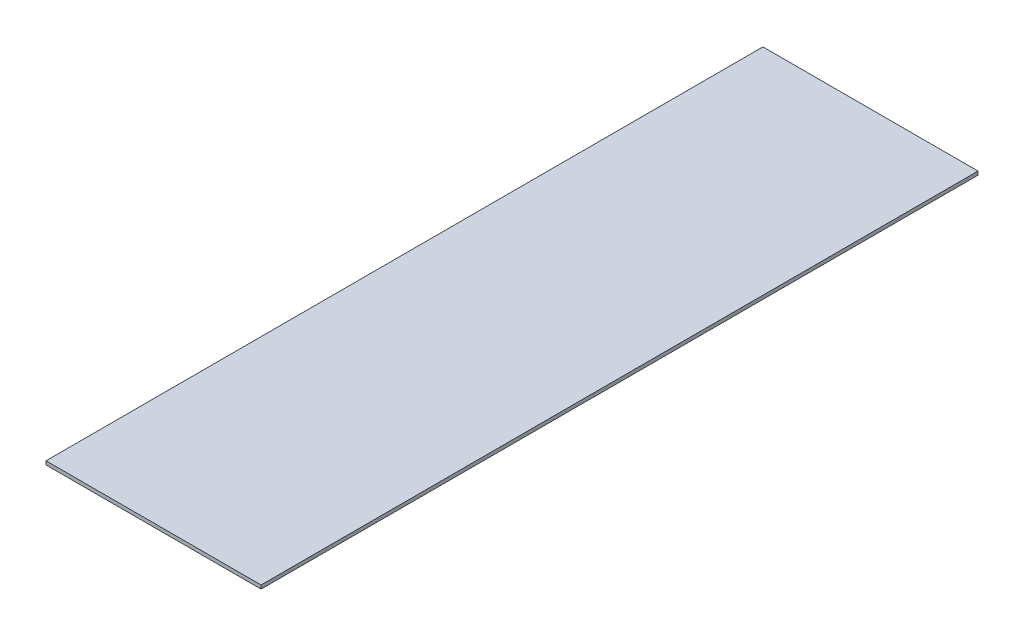
SolidWorks part; units mm, degrees
ref_plane "Front" through (0, 0, 0) normal (0, 0, 1) x (1, 0, 0)
ref_plane "Top" through (0, 0, 0) normal (0, 1, 0) x (1, 0, 0)
ref_plane "Right" through (0, 0, 0) normal (1, 0, 0) x (0, 0, -1)
sketch "Sketch1" plane through (0, 0, 0) normal (0, 1, 0) x (1, 0, 0)
  line L0 (-35.8245, 0) -> (130.6871, 0) construction
  line L2 (0, -100) -> (60, -100)
  line L3 (0, -100) -> (0, 100)
  line L4 (0, 100) -> (60, 100)
  line L5 (60, -100) -> (60, 100)
  dimension "D1" = 60
  dimension "D2" = 200
extrude "Boss-Extrude1" add sketch "Sketch1" along normal blind 1
